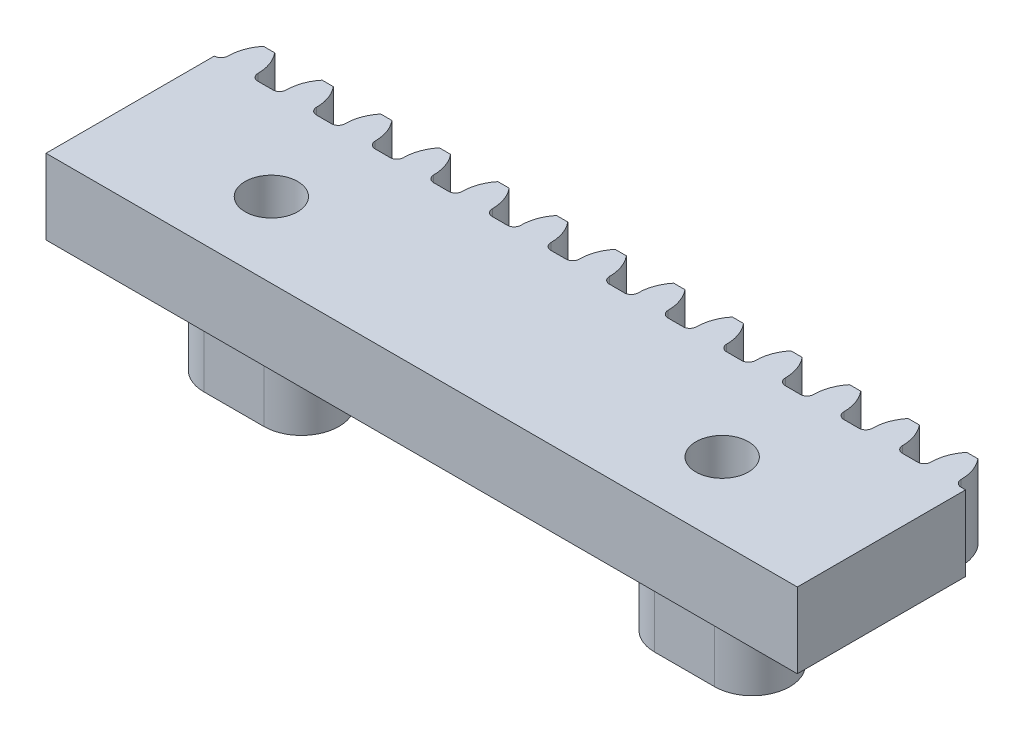
SolidWorks part; units mm, degrees
ref_plane "Front Plane" through (0, 0, 0) normal (0, 0, 1) x (1, 0, 0)
ref_plane "Top Plane" through (0, 0, 0) normal (0, 1, 0) x (1, 0, 0)
ref_plane "Right Plane" through (0, 0, 0) normal (1, 0, 0) x (0, 0, -1)
sketch "Sketch1" plane through (0, 0, 0) normal (0, 1, 0) x (1, 0, 0)
  line L0 (0, 0) -> (50, 0)
  line L1 (50, 0) -> (50, 11.2)
  line L2 (50, 12.05) -> (0, 12.05) construction
  line L3 (0, 11.2) -> (0, 0)
  line L4 (0, 11.2) -> (50, 11.2) construction
  line L5 (50, 13.4) -> (0, 13.4) construction
  line L6 (0, 11.65) -> (50, 11.65) construction
  line L7 (1.075, 13.4) -> (1.825, 13.4)
  line L8 (1.45, 13.4) -> (1.45, 11.2) construction
  line L9 (2.9, 11.2) -> (3.9, 11.2)
  line L10 (6.8, 11.2) -> (7.8, 11.2)
  line L11 (4.975, 13.4) -> (5.725, 13.4)
  line L12 (5.35, 13.4) -> (5.35, 11.2) construction
  line L13 (10.7, 11.2) -> (11.7, 11.2)
  line L14 (8.875, 13.4) -> (9.625, 13.4)
  line L15 (9.25, 13.4) -> (9.25, 11.2) construction
  line L16 (14.6, 11.2) -> (15.6, 11.2)
  line L17 (12.775, 13.4) -> (13.525, 13.4)
  line L18 (13.15, 13.4) -> (13.15, 11.2) construction
  line L19 (18.5, 11.2) -> (19.5, 11.2)
  line L20 (16.675, 13.4) -> (17.425, 13.4)
  line L21 (17.05, 13.4) -> (17.05, 11.2) construction
  line L22 (22.4, 11.2) -> (23.4, 11.2)
  line L23 (20.575, 13.4) -> (21.325, 13.4)
  line L24 (20.95, 13.4) -> (20.95, 11.2) construction
  line L25 (26.3, 11.2) -> (27.3, 11.2)
  line L26 (24.475, 13.4) -> (25.225, 13.4)
  line L27 (24.85, 13.4) -> (24.85, 11.2) construction
  line L28 (30.2, 11.2) -> (31.2, 11.2)
  line L29 (28.375, 13.4) -> (29.125, 13.4)
  line L30 (28.75, 13.4) -> (28.75, 11.2) construction
  line L31 (34.1, 11.2) -> (35.1, 11.2)
  line L32 (32.275, 13.4) -> (33.025, 13.4)
  line L33 (32.65, 13.4) -> (32.65, 11.2) construction
  line L34 (38, 11.2) -> (39, 11.2)
  line L35 (36.175, 13.4) -> (36.925, 13.4)
  line L36 (36.55, 13.4) -> (36.55, 11.2) construction
  line L37 (41.9, 11.2) -> (42.9, 11.2)
  line L38 (40.075, 13.4) -> (40.825, 13.4)
  line L39 (40.45, 13.4) -> (40.45, 11.2) construction
  line L48 (45.8, 11.2) -> (46.8, 11.2)
  line L51 (43.975, 13.4) -> (44.725, 13.4)
  line L54 (44.35, 13.4) -> (44.35, 11.2) construction
  line L55 (61.4, 11.2) -> (62.4, 11.2) [skipped]
  line L68 (49.7, 11.2) -> (50, 11.2)
  line L69 (47.875, 13.4) -> (48.625, 13.4)
  line L70 (48.25, 13.4) -> (48.25, 11.2) construction
  line L75 (45.8, 11.2) -> (46.8, 11.2) [skipped]
  line L76 (49.7, 11.2) -> (50.7, 11.2) [skipped]
  line L77 (47.875, 13.4) -> (48.625, 13.4) [skipped]
  line L78 (53.6, 11.2) -> (54.6, 11.2) [skipped]
  line L79 (51.775, 13.4) -> (52.525, 13.4) [skipped]
  line L80 (57.5, 11.2) -> (58.5, 11.2) [skipped]
  line L81 (55.675, 13.4) -> (56.425, 13.4) [skipped]
  line L82 (59.575, 13.4) -> (60.325, 13.4) [skipped]
  line L83 (48.25, 13.4) -> (48.25, 11.2) construction
  line L84 (52.15, 13.4) -> (52.15, 11.2) construction
  line L85 (56.05, 13.4) -> (56.05, 11.2) construction
  line L86 (59.95, 13.4) -> (59.95, 11.2) construction
  line L87 (43.975, 13.4) -> (44.725, 13.4) [skipped]
  line L88 (44.35, 13.4) -> (44.35, 11.2) construction
  arc A0 (0, 11.2) -> (0.45, 11.65) centre (0.0007, 11.6493) ccw
  arc A1 (0.45, 11.65) -> (1.075, 13.4) centre (3.2, 11.6545) cw
  arc A2 (2.45, 11.65) -> (1.825, 13.4) centre (-0.3, 11.6545) ccw
  arc A3 (2.9, 11.2) -> (2.45, 11.65) centre (2.8993, 11.6493) cw
  arc A4 (6.8, 11.2) -> (6.35, 11.65) centre (6.7993, 11.6493) cw
  arc A5 (6.35, 11.65) -> (5.725, 13.4) centre (3.6, 11.6545) ccw
  arc A6 (4.35, 11.65) -> (4.975, 13.4) centre (7.1, 11.6545) cw
  arc A7 (3.9, 11.2) -> (4.35, 11.65) centre (3.9007, 11.6493) ccw
  arc A8 (10.7, 11.2) -> (10.25, 11.65) centre (10.6993, 11.6493) cw
  arc A9 (10.25, 11.65) -> (9.625, 13.4) centre (7.5, 11.6545) ccw
  arc A10 (8.25, 11.65) -> (8.875, 13.4) centre (11, 11.6545) cw
  arc A11 (7.8, 11.2) -> (8.25, 11.65) centre (7.8007, 11.6493) ccw
  arc A12 (14.6, 11.2) -> (14.15, 11.65) centre (14.5993, 11.6493) cw
  arc A13 (14.15, 11.65) -> (13.525, 13.4) centre (11.4, 11.6545) ccw
  arc A14 (12.15, 11.65) -> (12.775, 13.4) centre (14.9, 11.6545) cw
  arc A15 (11.7, 11.2) -> (12.15, 11.65) centre (11.7007, 11.6493) ccw
  arc A16 (18.5, 11.2) -> (18.05, 11.65) centre (18.4993, 11.6493) cw
  arc A17 (18.05, 11.65) -> (17.425, 13.4) centre (15.3, 11.6545) ccw
  arc A18 (16.05, 11.65) -> (16.675, 13.4) centre (18.8, 11.6545) cw
  arc A19 (15.6, 11.2) -> (16.05, 11.65) centre (15.6007, 11.6493) ccw
  arc A20 (22.4, 11.2) -> (21.95, 11.65) centre (22.3993, 11.6493) cw
  arc A21 (21.95, 11.65) -> (21.325, 13.4) centre (19.2, 11.6545) ccw
  arc A22 (19.95, 11.65) -> (20.575, 13.4) centre (22.7, 11.6545) cw
  arc A23 (19.5, 11.2) -> (19.95, 11.65) centre (19.5007, 11.6493) ccw
  arc A24 (26.3, 11.2) -> (25.85, 11.65) centre (26.2993, 11.6493) cw
  arc A25 (25.85, 11.65) -> (25.225, 13.4) centre (23.1, 11.6545) ccw
  arc A26 (23.85, 11.65) -> (24.475, 13.4) centre (26.6, 11.6545) cw
  arc A27 (23.4, 11.2) -> (23.85, 11.65) centre (23.4007, 11.6493) ccw
  arc A28 (30.2, 11.2) -> (29.75, 11.65) centre (30.1993, 11.6493) cw
  arc A29 (29.75, 11.65) -> (29.125, 13.4) centre (27, 11.6545) ccw
  arc A30 (27.75, 11.65) -> (28.375, 13.4) centre (30.5, 11.6545) cw
  arc A31 (27.3, 11.2) -> (27.75, 11.65) centre (27.3007, 11.6493) ccw
  arc A32 (34.1, 11.2) -> (33.65, 11.65) centre (34.0993, 11.6493) cw
  arc A33 (33.65, 11.65) -> (33.025, 13.4) centre (30.9, 11.6545) ccw
  arc A34 (31.65, 11.65) -> (32.275, 13.4) centre (34.4, 11.6545) cw
  arc A35 (31.2, 11.2) -> (31.65, 11.65) centre (31.2007, 11.6493) ccw
  arc A36 (38, 11.2) -> (37.55, 11.65) centre (37.9993, 11.6493) cw
  arc A37 (37.55, 11.65) -> (36.925, 13.4) centre (34.8, 11.6545) ccw
  arc A38 (35.55, 11.65) -> (36.175, 13.4) centre (38.3, 11.6545) cw
  arc A39 (35.1, 11.2) -> (35.55, 11.65) centre (35.1007, 11.6493) ccw
  arc A40 (41.9, 11.2) -> (41.45, 11.65) centre (41.8993, 11.6493) cw
  arc A41 (41.45, 11.65) -> (40.825, 13.4) centre (38.7, 11.6545) ccw
  arc A42 (39.45, 11.65) -> (40.075, 13.4) centre (42.2, 11.6545) cw
  arc A43 (39, 11.2) -> (39.45, 11.65) centre (39.0007, 11.6493) ccw
  arc A85 (45.8, 11.2) -> (45.35, 11.65) centre (45.7993, 11.6493) cw
  arc A86 (45.35, 11.65) -> (44.725, 13.4) centre (42.6, 11.6545) ccw
  arc A87 (43.35, 11.65) -> (43.975, 13.4) centre (46.1, 11.6545) cw
  arc A88 (42.9, 11.2) -> (43.35, 11.65) centre (42.9007, 11.6493) ccw
  arc A89 (49.7, 11.2) -> (49.25, 11.65) centre (49.6993, 11.6493) cw
  arc A90 (49.25, 11.65) -> (48.625, 13.4) centre (46.5, 11.6545) ccw
  arc A92 (47.25, 11.65) -> (47.875, 13.4) centre (50, 11.6545) cw
  arc A93 (46.8, 11.2) -> (47.25, 11.65) centre (46.8007, 11.6493) ccw
  arc A98 (49.7, 11.2) -> (49.25, 11.65) centre (49.6993, 11.6493) cw [skipped]
  arc A99 (49.25, 11.65) -> (48.625, 13.4) centre (46.5, 11.6545) ccw [skipped]
  arc A100 (47.25, 11.65) -> (47.875, 13.4) centre (50, 11.6545) cw [skipped]
  arc A101 (46.8, 11.2) -> (47.25, 11.65) centre (46.8007, 11.6493) ccw [skipped]
  arc A102 (53.6, 11.2) -> (53.15, 11.65) centre (53.5993, 11.6493) cw [skipped]
  arc A103 (53.15, 11.65) -> (52.525, 13.4) centre (50.4, 11.6545) ccw [skipped]
  arc A104 (51.15, 11.65) -> (51.775, 13.4) centre (53.9, 11.6545) cw [skipped]
  arc A105 (50.7, 11.2) -> (51.15, 11.65) centre (50.7007, 11.6493) ccw [skipped]
  arc A106 (57.5, 11.2) -> (57.05, 11.65) centre (57.4993, 11.6493) cw [skipped]
  arc A107 (57.05, 11.65) -> (56.425, 13.4) centre (54.3, 11.6545) ccw [skipped]
  arc A108 (55.05, 11.65) -> (55.675, 13.4) centre (57.8, 11.6545) cw [skipped]
  arc A109 (54.6, 11.2) -> (55.05, 11.65) centre (54.6007, 11.6493) ccw [skipped]
  arc A110 (61.4, 11.2) -> (60.95, 11.65) centre (61.3993, 11.6493) cw [skipped]
  arc A111 (60.95, 11.65) -> (60.325, 13.4) centre (58.2, 11.6545) ccw [skipped]
  arc A112 (58.95, 11.65) -> (59.575, 13.4) centre (61.7, 11.6545) cw [skipped]
  arc A113 (58.5, 11.2) -> (58.95, 11.65) centre (58.5007, 11.6493) ccw [skipped]
  arc A114 (45.8, 11.2) -> (45.35, 11.65) centre (45.7993, 11.6493) cw [skipped]
  arc A115 (44.9909, 13.0131) -> (44.4684, 13.6722) centre (42.6, 11.6545) ccw [skipped]
  arc A116 (43.35, 11.65) -> (43.975, 13.4) centre (46.1, 11.6545) cw [skipped]
  arc A117 (42.9, 11.2) -> (43.35, 11.65) centre (42.9007, 11.6493) ccw [skipped]
  dimension "D11" = 2.75
  dimension "D2" = 50
  dimension "D3" = 2.2
  dimension "D4" = 0.4
  dimension "D5" = 0.45
  dimension "D6" = 0.75
  dimension "D7" = 2
  dimension "D8" = 2.9
  dimension "D10" = 1
  dimension "D12" = 13.4
  dimension "D9" = 16
extrude "Boss-Extrude1" add sketch "Sketch1" along normal blind 5
sketch "Sketch2" plane through (0, 0, 0) normal (0, -1, 0) x (1, 0, 0)
  line L0 (12, -7.5) -> (8, -7.5)
  line L1 (8, -2.5) -> (12, -2.5)
  line L2 (0, 0) -> (50, 0) construction
  line L3 (42, -7.5) -> (38, -7.5)
  line L4 (38, -2.5) -> (42, -2.5)
  line L5 (8, -5) -> (0, -5) construction
  line L6 (0, -11.2) -> (0, 0) construction
  line L7 (42, -5) -> (50, -5) construction
  line L8 (50, 0) -> (50, -11.2) construction
  arc A0 (8, -7.5) -> (8, -2.5) centre (8, -5) cw
  arc A1 (12, -2.5) -> (12, -7.5) centre (12, -5) cw
  circle A2 centre (10, -5) radius 1.75
  arc A3 (38, -7.5) -> (38, -2.5) centre (38, -5) cw
  arc A4 (42, -2.5) -> (42, -7.5) centre (42, -5) cw
  circle A5 centre (40, -5) radius 1.75
  point P11 (10, -7.5)
  point P20 (40, -7.5)
  dimension "D1" = 3.5
  dimension "D2" = 5
  dimension "D3" = 2.5
  dimension "D4" = 4
  dimension "D6" = 30
  dimension "D5" = 2
extrude "Boss-Extrude2" add sketch "Sketch2" along normal blind 6
sketch "Sketch3" plane through (0, 0, 0) normal (0, -1, 0) x (1, 0, 0)
  circle A0 centre (40, -5) radius 1.75 construction
  circle A1 centre (10, -5) radius 1.75 construction
  circle A2 centre (40, -5) radius 1.75
  circle A3 centre (10, -5) radius 1.75
extrude "Cut-Extrude1" cut sketch "Sketch3" against normal up to next
